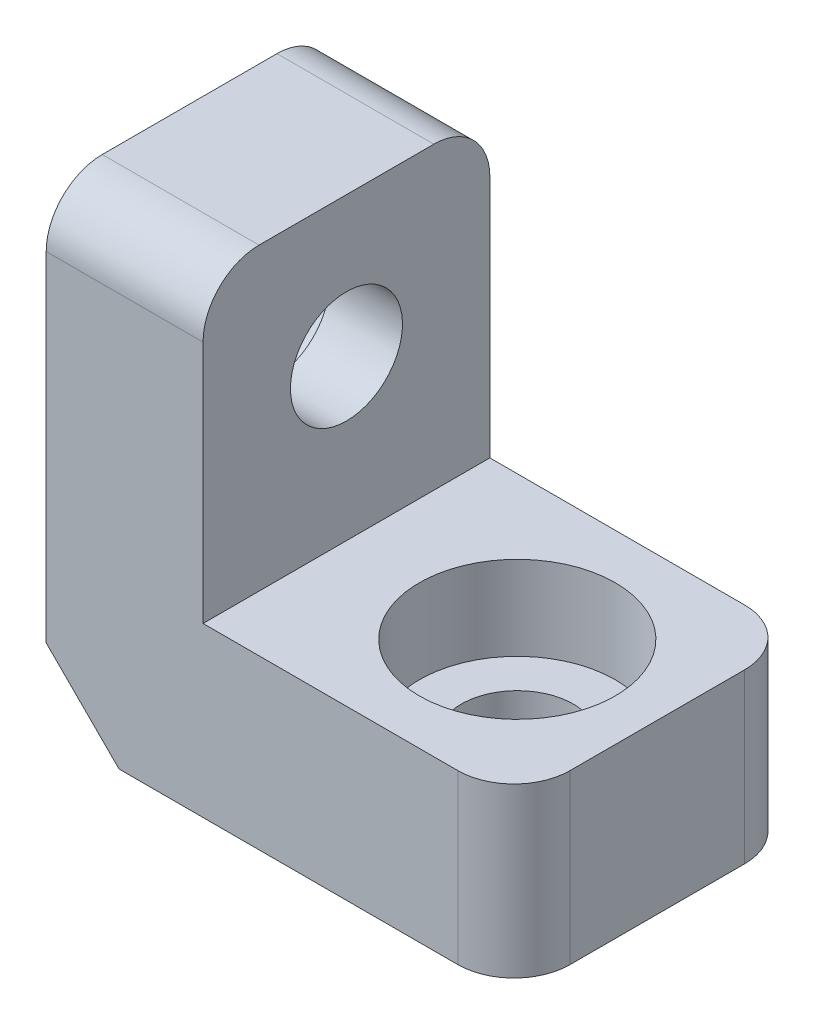
SolidWorks part; units mm, degrees
ref_plane "Plan de face" through (0, 0, 0) normal (0, 0, 1) x (1, 0, 0)
ref_plane "Plan de dessus" through (0, 0, 0) normal (0, 1, 0) x (1, 0, 0)
ref_plane "Plan de droite" through (0, 0, 0) normal (1, 0, 0) x (0, 0, -1)
sketch "Esquisse1" plane through (0, 0, 0) normal (0, 0, 1) x (1, 0, 0)
  line L0 (0, 0) -> (0, 8.35)
  line L1 (0, 8.35) -> (2.8, 8.35)
  line L2 (2.8, 8.35) -> (2.8, 3)
  line L3 (2.8, 3) -> (8.35, 3)
  line L4 (8.35, 3) -> (8.35, 0)
  line L5 (8.35, 0) -> (0, 0)
  dimension "D1" = 8.35
  dimension "D2" = 2.8
  dimension "D3" = 3
extrude "Boss.-Extru.1" add sketch "Esquisse1" along normal blind 5.12
hole_wizard "Chambrage pour vis à tête hexagonale M21" positions "Esquisse2" profile "Esquisse3" counterbore size "M2" standard "ISO" end condition up to next
sketch "Esquisse2" plane through (0, 3, 0) normal (0, -1, 0) x (-1, 0, 0)
  line L0 (-8.35, -5.12) -> (-8.35, 0) construction
  line L1 (-8.35, -2.56) -> (0, -2.56) construction
  line L2 (0, -5.12) -> (0, 0) construction
  point P0 (-5.85, -2.56)
  dimension "D1" = 2.5
sketch "Esquisse3" plane through (5.85, 3, 2.56) normal (1, 0, 0) x (0, 0, 1)
  line L0 (0, 0) -> (0, 3)
  line L1 (0, 3) -> (1, 3)
  line L3 (1, 3) -> (1, 1.5)
  line L4 (1, 1.5) -> (1.75, 1.5)
  line L5 (1.75, 1.5) -> (1.75, 0)
  line L7 (1.75, 0) -> (0, 0)
  line L11 (0, -6.35) -> (0, 107.95) construction
  dimension "Diamètre du perçage jusqu'au prochain" = 2
  dimension "Profondeur du perçage jusqu'au prochain" = 3
  dimension "Diamètre du chambrage" = 3.5
  dimension "Profondeur du chambrage" = 1.5
hole_wizard "Chambrage pour vis à tête hexagonale M22" positions "Esquisse4" profile "Esquisse5" counterbore size "M2" standard "ISO" end condition up to next
sketch "Esquisse4" plane through (0, 0, 0) normal (-1, 0, 0) x (0, 0, 1)
  line L0 (2.56, 8.35) -> (2.56, 0) construction
  line L1 (5.12, 8.35) -> (0, 8.35) construction
  line L2 (5.12, 0) -> (0, 0) construction
  point P0 (2.56, 5.85)
  dimension "D1" = 2.5
sketch "Esquisse5" plane through (0, 5.85, 2.56) normal (0, 1, 0) x (0, 0, 1)
  line L0 (0, 0) -> (0, 2.8)
  line L1 (0, 2.8) -> (1, 2.8)
  line L3 (1, 2.8) -> (1, 1.5)
  line L4 (1, 1.5) -> (1.75, 1.5)
  line L5 (1.75, 1.5) -> (1.75, 0)
  line L7 (1.75, 0) -> (0, 0)
  line L11 (0, -6.35) -> (0, 107.95) construction
  dimension "Diamètre du perçage jusqu'au prochain" = 2
  dimension "Profondeur du perçage jusqu'au prochain" = 2.8
  dimension "Diamètre du chambrage" = 3.5
  dimension "Profondeur du chambrage" = 1.5
chamfer "Chanfrein1" distance 1.3 1 edges at (0, 0, 2.56)
fillet "Congé1" radius 1 4 edges at (1.4, 8.35, 0) (1.4, 8.35, 5.12) (8.35, 1.5, 0) (8.35, 1.5, 5.12)
